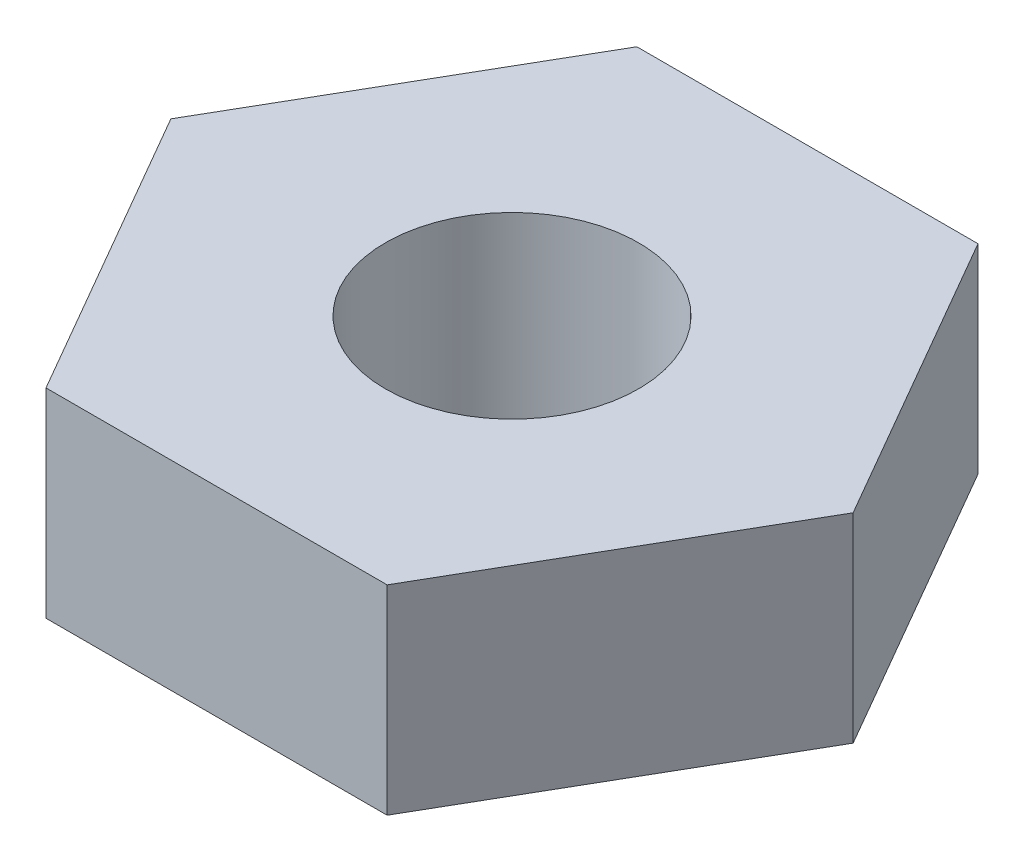
SolidWorks part; units mm, degrees
ref_plane "Front Plane" through (0, 0, 0) normal (0, 0, 1) x (1, 0, 0)
ref_plane "Top Plane" through (0, 0, 0) normal (0, 1, 0) x (1, 0, 0)
ref_plane "Right Plane" through (0, 0, 0) normal (1, 0, 0) x (0, 0, -1)
sketch "Sketch1" plane through (0, 0, 0) normal (0, 1, 0) x (1, 0, 0)
  line L1 (4.4456, 0) -> (2.2228, 3.85)
  line L2 (2.2228, 3.85) -> (-2.2228, 3.85)
  line L3 (-2.2228, 3.85) -> (-4.4456, 0)
  line L4 (-4.4456, 0) -> (-2.2228, -3.85)
  line L5 (-2.2228, -3.85) -> (2.2228, -3.85)
  line L6 (2.2228, -3.85) -> (4.4456, 0)
  circle A0 centre (0, 0) radius 1.65
  circle A1 centre (0, 0) radius 3.85 construction
  dimension "D1" = 3.3
  dimension "D2" = 7.7
extrude "Boss-Extrude1" add sketch "Sketch1" along normal mid plane 2.6
